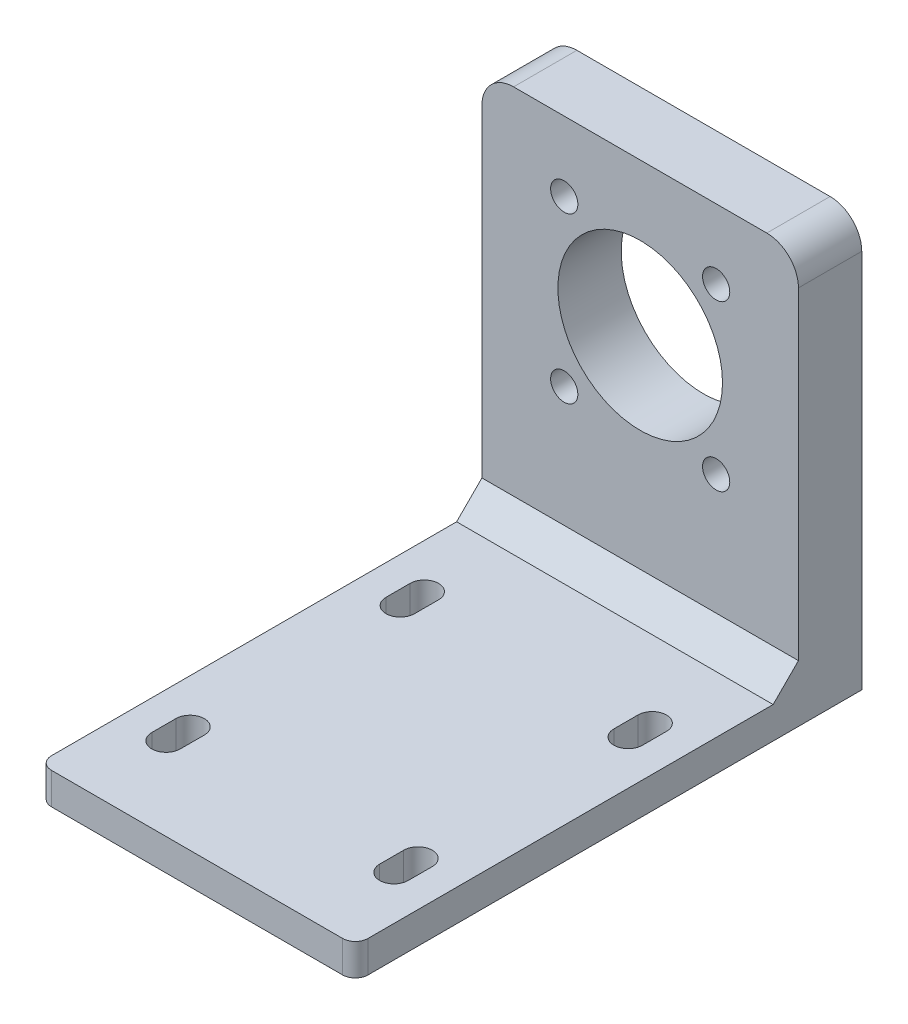
SolidWorks part; units mm, degrees
ref_plane "前视基准面" through (0, 0, 0) normal (0, 0, 1) x (1, 0, 0)
ref_plane "上视基准面" through (0, 0, 0) normal (0, 1, 0) x (1, 0, 0)
ref_plane "右视基准面" through (0, 0, 0) normal (1, 0, 0) x (0, 0, -1)
sketch "草图1" plane through (0, 0, 0) normal (0, 0, 1) x (1, 0, 0)
  line L0 (25, -30) -> (25, -27)
  line L5 (-25, 30) -> (25, 30)
  line L6 (-25, 30) -> (-25, -30)
  line L7 (-25, -30) -> (25, -30)
  line L8 (25, 30) -> (25, -30)
  line L9 (-25, 30) -> (25, -30) construction
  line L10 (-25, -30) -> (25, 30) construction
  line L11 (-25, 30) -> (-25, 19)
  line L12 (-25, 19) -> (-12, 19) construction
  line L13 (25, -27) -> (25, -7)
  line L14 (25, -7) -> (12, -7) construction
  line L15 (25, 30) -> (48.1016, 30)
  line L16 (48.1016, 30) -> (48.1016, 6) construction
  line L17 (48.1016, 6) -> (-25, 6)
  line L18 (0, 30) -> (0, 6)
  circle A0 centre (-12, 19) radius 2.15
  circle A1 centre (12, -7) radius 2.15
  circle A2 centre (12, 19) radius 2.15
  circle A3 centre (-12, -7) radius 2.15
  circle A4 centre (0, 6) radius 13
  point P0 (0, 0)
  dimension "D3" = 4.3
  dimension "D4" = 4.3
  dimension "D5" = 26
  dimension "D1" = 50
  dimension "D2" = 60
extrude "凸台-拉伸1" add sketch "草图1" along normal blind 10 contours A4 L17 L8 L5 L18 A2 | A4 L18 L5 L6 L17 A0 | A4 L17 L6 L7 L0 L8 A1 A3
sketch "草图2" plane through (0, -30, 0) normal (0, -1, 0) x (1, 0, 0)
  line L0 (-25, 10) -> (25, 10)
  line L1 (25, 10) -> (25, 0)
  line L2 (25, 0) -> (-25, 0)
  line L3 (-25, 0) -> (-25, 10)
extrude "凸台-拉伸2" add sketch "草图2" along normal blind 5
sketch "草图3" plane through (0, 0, 10) normal (0, 0, 1) x (1, 0, 0)
  line L0 (25, -35) -> (25, -30)
  line L1 (25, 30) -> (25, -35) construction
  line L2 (25, -30) -> (-25, -30)
  line L3 (-25, 30) -> (-25, -35) construction
  line L4 (-25, -30) -> (-25, -35)
  line L5 (-25, -35) -> (25, -35)
extrude "凸台-拉伸3" add sketch "草图3" along normal blind 70
sketch "草图8" plane through (0, -30, 0) normal (0, 1, 0) x (1, 0, 0)
  line L0 (25, -10) -> (25, -13)
  line L1 (-25, -45) -> (-18, -45)
  line L2 (25, -80) -> (25, -10) construction
  line L3 (25, -80) -> (25, -65)
  line L4 (25, -80) -> (25, -28)
  line L5 (-25, -80) -> (-25, -10) construction
  line L6 (-18, -45) -> (-18, -65)
  line L7 (-18, -65) -> (25, -65)
  line L8 (-18, -66.9) -> (-18, -63.1) construction
  line L9 (-20.25, -66.9) -> (-20.25, -63.1)
  line L10 (-15.75, -66.9) -> (-15.75, -63.1)
  line L11 (25, -28) -> (-18, -28)
  line L12 (-18, -26.1) -> (-18, -29.9) construction
  line L13 (-15.75, -26.1) -> (-15.75, -29.9)
  line L14 (-20.25, -26.1) -> (-20.25, -29.9)
  line L15 (0, -10) -> (0, -80)
  line L16 (25, -10) -> (-25, -10) construction
  line L17 (25, -80) -> (-25, -80) construction
  line L18 (18, -66.9) -> (18, -63.1) construction
  line L19 (20.25, -66.9) -> (20.25, -63.1)
  line L20 (15.75, -66.9) -> (15.75, -63.1)
  line L21 (18, -26.1) -> (18, -29.9) construction
  line L22 (15.75, -26.1) -> (15.75, -29.9)
  line L23 (20.25, -26.1) -> (20.25, -29.9)
  arc A0 (-20.25, -66.9) -> (-15.75, -66.9) centre (-18, -66.9) ccw
  arc A1 (-15.75, -63.1) -> (-20.25, -63.1) centre (-18, -63.1) ccw
  arc A2 (-15.75, -26.1) -> (-20.25, -26.1) centre (-18, -26.1) ccw
  arc A3 (-20.25, -29.9) -> (-15.75, -29.9) centre (-18, -29.9) ccw
  arc A4 (20.25, -66.9) -> (15.75, -66.9) centre (18, -66.9) cw
  arc A5 (15.75, -63.1) -> (20.25, -63.1) centre (18, -63.1) cw
  arc A6 (15.75, -26.1) -> (20.25, -26.1) centre (18, -26.1) cw
  arc A7 (20.25, -29.9) -> (15.75, -29.9) centre (18, -29.9) cw
  point P16 (-18, -65)
  point P24 (-18, -28)
  point P37 (18, -65)
  point P44 (18, -28)
  dimension "D1" = 15
  dimension "D2" = 15
  dimension "D3" = 4.5
  dimension "D4" = 8.3
  dimension "D5" = 4.5
  dimension "D6" = 8.3
extrude "切除-拉伸1" cut sketch "草图8" against normal blind 20 and the other way through all
fillet "圆角1" radius 5 2 edges at (-25, 30, 5) (25, 30, 5)
fillet "圆角2" radius 2 2 edges at (25, -32.5, 80) (-25, -32.5, 80)
sketch "草图9" plane through (0, -30, 0) normal (0, 1, 0) x (1, 0, 0)
  line L0 (25, -10) -> (25, -14)
  line L1 (25, -78) -> (25, -10) construction
  line L2 (25, -14) -> (21, -14)
  line L3 (21, -14) -> (21, -10)
  line L4 (25, -10) -> (-25, -10) construction
  line L5 (21, -10) -> (25, -10)
extrude "凸台-拉伸4" add sketch "草图9" along normal blind 4
sketch "草图10" plane through (21, 0, 0) normal (-1, 0, 0) x (0, 0, 1)
  line L0 (10, -26) -> (14, -26)
  line L1 (14, -26) -> (14, -30)
  line L2 (14, -30) -> (10, -30)
  line L3 (10, -30) -> (10, -26)
sketch "草图13" plane through (21, 0, 0) normal (-1, 0, 0) x (0, 0, 1)
  line L0 (10, -26) -> (14, -26)
  line L1 (14, -26) -> (14, -30)
  line L2 (14, -30) -> (10, -30)
  line L3 (10, -30) -> (10, -26)
extrude "凸台-拉伸6" add sketch "草图13" along normal blind 46
sketch "草图14" plane through (25, 0, 0) normal (1, 0, 0) x (0, 0, -1)
  line L0 (-10, -26) -> (-14, -30)
  line L1 (-14, -30) -> (-14, -26)
  line L2 (-14, -26) -> (-10, -26)
extrude "切除-拉伸2" cut sketch "草图14" against normal through all
